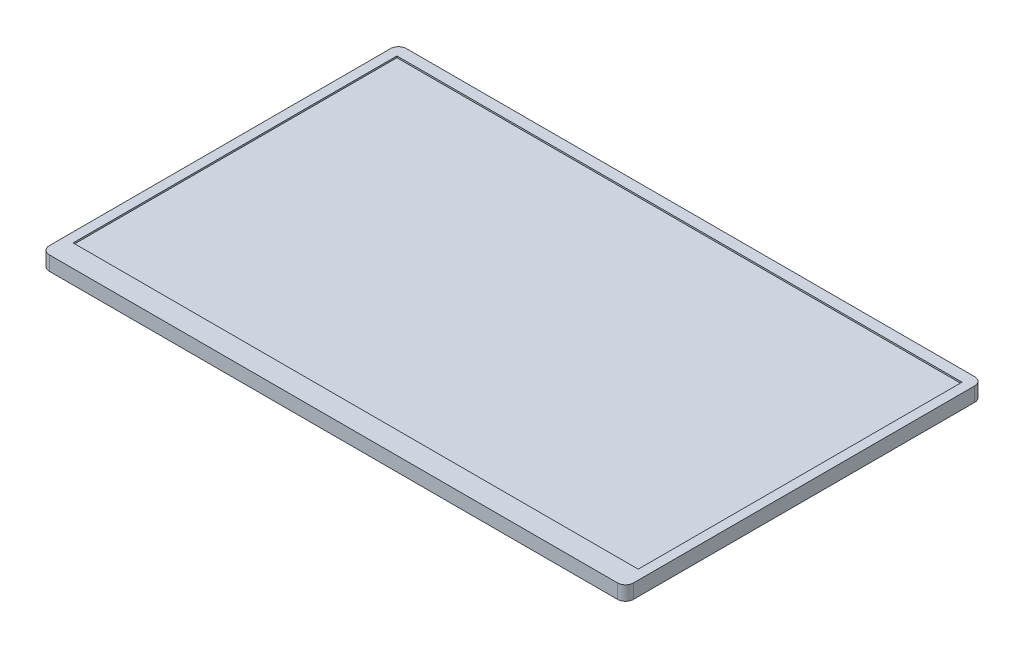
SolidWorks part; units mm, degrees
ref_plane "前视基准面" through (0, 0, 0) normal (0, 0, 1) x (1, 0, 0)
ref_plane "上视基准面" through (0, 0, 0) normal (0, 1, 0) x (1, 0, 0)
ref_plane "右视基准面" through (0, 0, 0) normal (1, 0, 0) x (0, 0, -1)
sketch "草图1" plane through (0, 0, 0) normal (0, 1, 0) x (1, 0, 0)
  line L1 (-184, 112.5) -> (184, 112.5)
  line L2 (-184, 112.5) -> (-184, -112.5)
  line L3 (-184, -112.5) -> (184, -112.5)
  line L4 (184, 112.5) -> (184, -112.5)
  dimension "D1" = 368
  dimension "D2" = 225
  dimension "D3" = 184
  dimension "D4" = 112.5
extrude "凸台-拉伸1" add sketch "草图1" along normal blind 9
fillet "圆角1" radius 5 4 edges at (184, 4.5, 112.5) (-184, 4.5, 112.5) (-184, 4.5, -112.5) (184, 4.5, -112.5)
sketch "草图2" plane through (0, 9, 0) normal (0, 1, 0) x (1, 0, 0)
  line L0 (-184, 107.5) -> (-184, -107.5) construction
  line L1 (-178, 105.5) -> (178, 105.5)
  line L2 (-178, 105.5) -> (-178, -98.5)
  line L3 (-178, -98.5) -> (178, -98.5)
  line L4 (178, 105.5) -> (178, -98.5)
  line L5 (179, 112.5) -> (-179, 112.5) construction
  dimension "D1" = 356
  dimension "D2" = 204
  dimension "D3" = 6
  dimension "D4" = 7
extrude "切除-拉伸1" cut sketch "草图2" against normal blind 1
